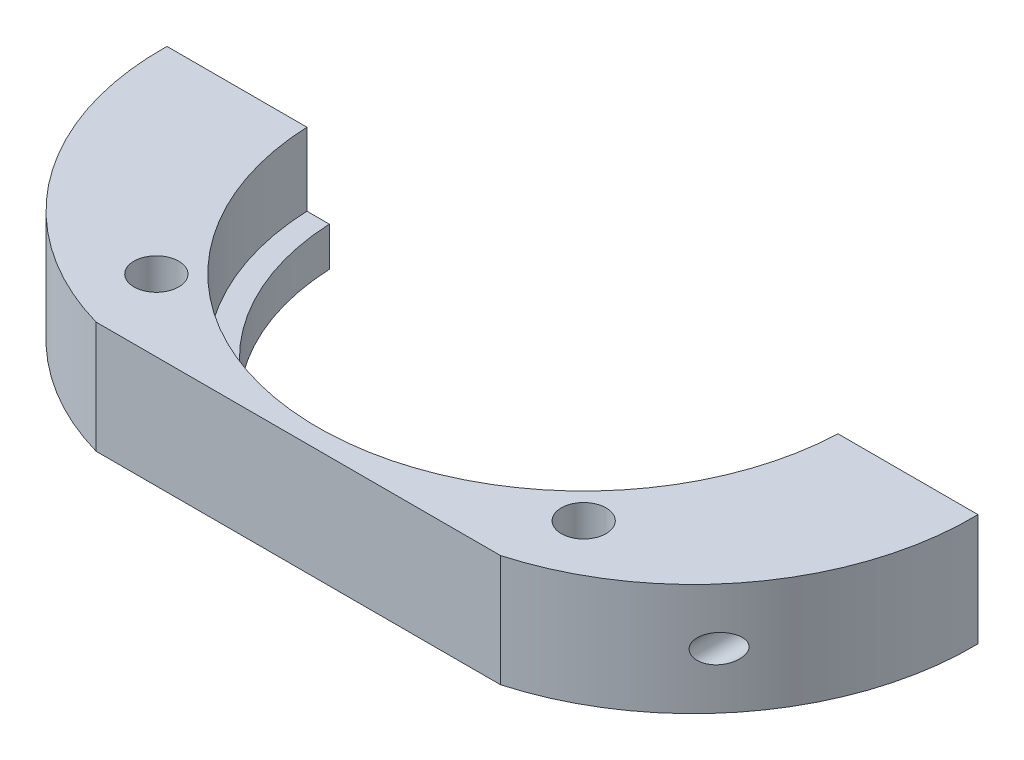
SolidWorks part; units mm, degrees
ref_plane "Front Plane" through (0, 0, 0) normal (0, 0, 1) x (1, 0, 0)
ref_plane "Top Plane" through (0, 0, 0) normal (0, 1, 0) x (1, 0, 0)
ref_plane "Right Plane" through (0, 0, 0) normal (1, 0, 0) x (0, 0, -1)
sketch "Sketch1" plane through (0, 0, 0) normal (0, 1, 0) x (1, 0, 0)
  circle A0 centre (0, 0) radius 62.5
  circle A1 centre (0, 0) radius 43.5
  dimension "D1" = 125
  dimension "D2" = 87
extrude "Boss-Extrude1" add sketch "Sketch1" along normal blind 20
sketch "Sketch2" plane through (0, 20, 0) normal (0, 1, 0) x (1, 0, 0)
  circle A0 centre (0, 0) radius 47.5
  dimension "D1" = 95
extrude "Cut-Extrude1" cut sketch "Sketch2" against normal blind 13
sketch "Sketch3" plane through (0, 20, 0) normal (0, 1, 0) x (1, 0, 0)
  line L0 (0, 0) -> (38.1838, 38.1838) construction
  line L1 (0, 0) -> (54, 0) construction
  circle A0 centre (0, 0) radius 54 construction
  circle A1 centre (38.1838, 38.1838) radius 4
  circle A2 centre (38.1838, -38.1838) radius 4
  circle A3 centre (-38.1838, -38.1838) radius 4
  circle A4 centre (-38.1838, 38.1838) radius 4
  point P14 (0, 0)
  dimension "D1" = 8
  dimension "D3" = 108
  dimension "D4" = 45
  dimension "D2" = 4
extrude "Cut-Extrude2" cut sketch "Sketch3" against normal through all
sketch "Sketch4" plane through (0, 20, 0) normal (0, 1, 0) x (1, 0, 0)
  line L0 (0, 0) -> (0, -2) construction
  line L7 (-75, -2) -> (75, -2)
  line L8 (-75, -2) -> (-75, 62.5)
  line L9 (-75, 62.5) -> (75, 62.5)
  line L10 (75, -2) -> (75, 62.5)
  line L11 (-36.1282, -62.5) -> (36.1282, -62.5)
  line L12 (-36.1282, -62.5) -> (-36.1282, -51)
  line L13 (-36.1282, -51) -> (36.1282, -51)
  line L14 (36.1282, -62.5) -> (36.1282, -51)
  circle A1 centre (0, 0) radius 62.5 construction
  dimension "D1" = 2
  dimension "D2" = 51
  dimension "D3" = 150
extrude "Cut-Extrude3" cut sketch "Sketch4" against normal through all
sketch "Sketch5" plane through (0, 20, 0) normal (0, 1, 0) x (1, 0, 0)
  line L0 (47.4579, -2) -> (62.468, -2) construction
  line L1 (54.9629, -2) -> (84.9629, -2)
  line L2 (54.9629, -2) -> (54.9629, -12)
  line L3 (54.9629, -12) -> (84.9629, -12)
  line L4 (84.9629, -2) -> (84.9629, -12)
  line L5 (-62.468, -2) -> (-47.4579, -2) construction
  line L6 (-54.9629, -2) -> (-84.9629, -2)
  line L7 (-54.9629, -2) -> (-54.9629, -12)
  line L8 (-54.9629, -12) -> (-84.9629, -12)
  line L9 (-84.9629, -2) -> (-84.9629, -12)
  dimension "D1" = 30
  dimension "D2" = 10
extrude "Boss-Extrude2" [suppressed] add sketch "Sketch5" against normal through all
fillet "Fillet1" [suppressed] radius 5
sketch "Sketch6" plane through (0, 20, 0) normal (0, 1, 0) x (1, 0, 0)
  line L0 (-72.468, -2) -> (72.468, -2)
  line L1 (47.4579, -2) -> (62.468, -2) construction
  line L2 (0, 0) -> (0, -2) construction
  line L9 (-47.4579, -2) -> (-62.468, -2)
  line L10 (-36.1282, -51) -> (36.1282, -51)
  line L11 (62.468, -2) -> (47.4579, -2)
  line L12 (-47.4579, -2) -> (-62.468, -2)
  line L13 (-36.1282, -51) -> (36.1282, -51)
  line L14 (62.468, -2) -> (47.4579, -2)
  arc A0 (36.1282, -51) -> (72.468, -2) centre (22.4761, -2.8999) ccw
  arc A1 (-36.1282, -51) -> (-72.468, -2) centre (-22.4761, -2.8999) cw
  arc A8 (-62.468, -2) -> (-36.1282, -51) centre (0, 0) ccw
  arc A9 (36.1282, -51) -> (62.468, -2) centre (0, 0) ccw
  arc A10 (-47.4579, -2) -> (47.4579, -2) centre (0, 0) ccw
  arc A11 (-62.468, -2) -> (-36.1282, -51) centre (0, 0) ccw
  arc A12 (36.1282, -51) -> (62.468, -2) centre (0, 0) ccw
  arc A13 (-47.4579, -2) -> (47.4579, -2) centre (0, 0) ccw
  arc M4 (-62.468, -2) -> (-36.1282, -51) centre (0, 0) ccw
  arc M6 (36.1282, -51) -> (62.468, -2) centre (0, 0) ccw
  dimension "D2" = 50
  dimension "D1" = 10
  dimension "D3" = 0
extrude "Boss-Extrude4" add sketch "Sketch6" against normal through all contours A1 L0 M4 | A0 L0 M6
sketch "Sketch7" plane through (0, 0, 2) normal (0, 0, -1) x (-1, 0, 0)
  line L0 (-72.468, 10) -> (-59.9629, 10) construction
  line L1 (-72.468, 0) -> (-72.468, 20) construction
  line L2 (-59.9629, 10) -> (-59.9629, 20) construction
  line L3 (-47.4579, 20) -> (-72.468, 20) construction
  circle A0 centre (-59.9629, 10) radius 2.5
  dimension "D1" = 5
extrude "Cut-Extrude4" cut sketch "Sketch7" against normal through all
sketch "Sketch8" plane through (0, 0, 2) normal (0, 0, -1) x (-1, 0, 0)
  line L0 (59.9629, 10) -> (59.9629, 20) construction
  line L1 (72.468, 20) -> (47.4579, 20) construction
  line L2 (59.9629, 10) -> (72.468, 10) construction
  line L3 (72.468, 0) -> (72.468, 20) construction
  circle A0 centre (59.9629, 10) radius 5
  dimension "D1" = 10
hole_wizard "M8 Tapped Hole1" positions "3DSketch3" profile "Sketch10" tap size "M8" standard "ISO"
sketch3d "3DSketch3"
  point P6 (-59.9629, 10, 2)
cosmetic thread "Hole Thread1" parameters "D1"=35, "D2"=8
sketch "Sketch10" plane through (-59.9629, 10, 2) normal (1, 0, 0) x (0, 1, 0)
  line L0 (0, 0) -> (0, 40.7929)
  line L1 (0, 40.7929) -> (3.4, 38.75)
  line L2 (3.4, 38.75) -> (3.4, 0.625)
  line L3 (3.4, 0.625) -> (4.025, 0)
  line L5 (4.025, 0) -> (0, 0)
  line L6 (-3.4, 0.625) -> (-4.025, 0) construction
  line L10 (0, 40.7929) -> (-3.4, 38.75) construction
  line L11 (0, -6.35) -> (0, 107.95) construction
  dimension "Tap Drill Dia." = 6.8
  dimension "Tap Drill Depth" = 38.75
  dimension "Near C'Sink Dia." = 8.05
  dimension "Near C'Sink Angle" = 90
  dimension "Drill Angle" = 118
hole_wizard "M8 Tapped Hole2" positions "3DSketch4" profile "Sketch11" tap size "M8" standard "ISO"
sketch3d "3DSketch4"
  line L0 (59.9629, 10, 32.9174) -> (59.9629, 10, 2) construction
  point P0 (59.9629, 10, 2)
sketch "Sketch11" plane through (59.9629, 10, 2) normal (1, 0, 0) x (0, 1, 0)
  line L0 (0, 0) -> (0, 21.7929)
  line L1 (0, 21.7929) -> (3.4, 19.75)
  line L2 (3.4, 19.75) -> (3.4, 0.625)
  line L3 (3.4, 0.625) -> (4.025, 0)
  line L5 (4.025, 0) -> (0, 0)
  line L6 (-3.4, 0.625) -> (-4.025, 0) construction
  line L10 (0, 21.7929) -> (-3.4, 19.75) construction
  line L11 (0, -6.35) -> (0, 107.95) construction
  dimension "Tap Drill Dia." = 6.8
  dimension "Tap Drill Depth" = 19.75
  dimension "Near C'Sink Dia." = 8.05
  dimension "Near C'Sink Angle" = 90
  dimension "Drill Angle" = 118
cosmetic thread "Hole Thread2" parameters "D1"=16, "D2"=8
